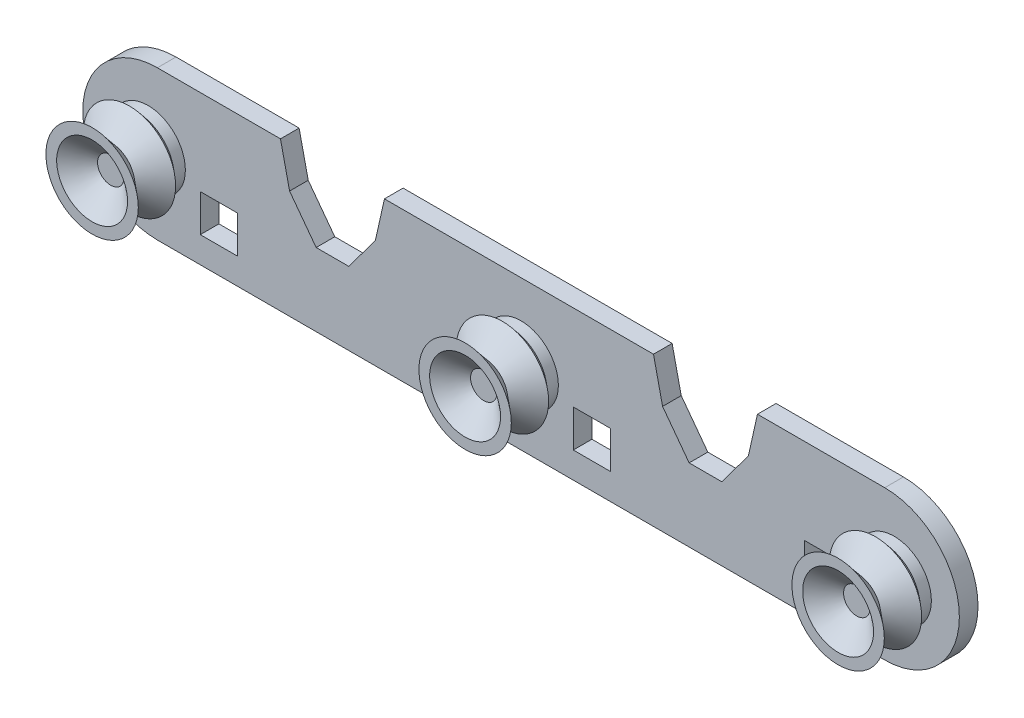
SolidWorks part; units mm, degrees
ref_plane "Plan de face" through (0, 0, 0) normal (0, 0, 1) x (1, 0, 0)
ref_plane "Plan de dessus" through (0, 0, 0) normal (0, 1, 0) x (1, 0, 0)
ref_plane "Plan de droite" through (0, 0, 0) normal (1, 0, 0) x (0, 0, -1)
sketch "Esquisse1" plane through (0, 0, 0) normal (0, 0, 1) x (1, 0, 0)
  line L0 (-98.7291, 0) -> (96.2709, 0) construction
  line L1 (-98.7291, 20) -> (96.2709, 20)
  line L2 (-98.7291, -20) -> (96.2709, -20)
  arc A0 (-98.7291, 20) -> (-98.7291, -20) centre (-98.7291, 0) ccw
  arc A1 (96.2709, -20) -> (96.2709, 20) centre (96.2709, 0) ccw
  circle A2 centre (-101.2291, 0) radius 5
  circle A3 centre (-1.2291, 0) radius 5
  circle A4 centre (98.7709, 0) radius 5
  point P3 (-1.2291, 0)
  point P8 (-118.7291, 0)
  point P9 (116.2709, 0)
  dimension "D1" = 235
  dimension "D2" = 20
  dimension "D3" = 10
  dimension "D4" = 10
  dimension "D5" = 10
  dimension "D6" = 100
  dimension "D7" = 100
extrude "Boss.-Extru.1" add sketch "Esquisse1" along normal blind 5
sketch "Esquisse2" plane through (0, 0, 5) normal (0, 0, 1) x (1, 0, 0)
  circle A0 centre (-101.2291, 0) radius 10
  circle A1 centre (-1.2291, 0) radius 10
  circle A2 centre (98.7709, 0) radius 10
  dimension "D1" = 20
  dimension "D2" = 3
extrude "Boss.-Extru.2" add sketch "Esquisse2" along normal blind 3
sketch "Esquisse3" plane through (0, 0, 8) normal (0, 0, 1) x (1, 0, 0)
  circle A0 centre (-101.2291, 0) radius 10
  circle A1 centre (-1.2291, 0) radius 10
  circle A2 centre (98.7709, 0) radius 10
  dimension "D1" = 3
extrude "Boss.-Extru.3" add sketch "Esquisse3" along normal blind 2 draft 50 draft outward yes
sketch "Esquisse4" plane through (0, 0, 10) normal (0, 0, 1) x (1, 0, 0)
  circle A0 centre (-101.2291, 0) radius 12.3835
  circle A1 centre (-1.2291, 0) radius 12.3835
  circle A2 centre (98.7709, 0) radius 12.3835
  dimension "D1" = 3
extrude "Boss.-Extru.4" add sketch "Esquisse4" along normal blind 5 draft 50
sketch "Esquisse5" plane through (0, 0, 15) normal (0, 0, 1) x (1, 0, 0)
  circle A0 centre (-101.2291, 0) radius 6.4247
  circle A1 centre (-1.2291, 0) radius 6.4247
  circle A2 centre (98.7709, 0) radius 6.4247
  dimension "D1" = 3
extrude "Boss.-Extru.5" add sketch "Esquisse5" along normal blind 5 draft 50 draft outward yes
sketch "Esquisse6" plane through (0, 0, 20) normal (0, 0, 1) x (1, 0, 0)
  circle A0 centre (-101.2291, 0) radius 9.5
  circle A1 centre (-1.2291, 0) radius 9.5
  circle A2 centre (98.7709, 0) radius 9.5
  dimension "D1" = 19
  dimension "D2" = 3
extrude "Enlèv. mat.-Extru.1" cut sketch "Esquisse6" against normal blind 5 draft 50
sketch "Esquisse7" plane through (0, 0, 0) normal (0, 0, -1) x (-1, 0, 0)
  line L0 (98.7291, -20) -> (-96.2709, -20) construction
  line L1 (-74.7709, -13) -> (-84.7709, -13)
  line L2 (-74.7709, -13) -> (-74.7709, -3)
  line L3 (-74.7709, -3) -> (-84.7709, -3)
  line L4 (-84.7709, -13) -> (-84.7709, -3)
  line L13 (65.7291, 20) -> (63.2907, 9.0964)
  line L14 (-12.7709, -13) -> (-22.7709, -13)
  line L15 (-12.7709, -13) -> (-12.7709, -3)
  line L16 (-12.7709, -3) -> (-22.7709, -3)
  line L17 (-22.7709, -13) -> (-22.7709, -3)
  line L18 (87.2291, -13) -> (77.2291, -13)
  line L19 (87.2291, -13) -> (87.2291, -3)
  line L20 (87.2291, -3) -> (77.2291, -3)
  line L21 (77.2291, -13) -> (77.2291, -3)
  line L22 (-96.2709, 20) -> (98.7291, 20) construction
  line L23 (63.2907, 9.0964) -> (56.1657, -0.4559)
  line L24 (56.1657, -0.4559) -> (47.4178, -0.4559) construction
  line L25 (51.7918, -0.4559) -> (51.7918, 22.851) construction
  line L30 (56.1657, -0.4559) -> (51.7918, -0.4559)
  line L31 (37.8545, 20) -> (40.2928, 9.0964)
  line L32 (40.2928, 9.0964) -> (47.4178, -0.4559)
  line L33 (47.4178, -0.4559) -> (51.7918, -0.4559)
  line L34 (65.7291, 20) -> (37.8545, 20)
  line L36 (-36.7093, 9.0964) -> (-43.8343, -0.4559)
  line L37 (-34.2709, 20) -> (-36.7093, 9.0964)
  line L38 (-52.5822, -0.4559) -> (-48.2082, -0.4559)
  line L39 (-43.8343, -0.4559) -> (-48.2082, -0.4559)
  line L40 (-59.7072, 9.0964) -> (-52.5822, -0.4559)
  line L41 (-62.1455, 20) -> (-59.7072, 9.0964)
  line L42 (-34.2709, 20) -> (-62.1455, 20)
  line L44 (-34.2709, 20) -> (-62.1455, 20) [skipped]
  circle A0 centre (-98.7709, 0) radius 5 construction
  circle A1 centre (1.2291, 0) radius 5 construction
  circle A2 centre (101.2291, 0) radius 5 construction
  point P16 (1.2291, 0)
  point P20 (101.2291, 0)
  point P31 (0, 0)
  point P32 (0, 0)
  point P36 (0, 0)
  point P39 (0, 0)
  dimension "D1" = 10
  dimension "D2" = 10
  dimension "D3" = 14
  dimension "D4" = 7
  dimension "D5" = 10
  dimension "D6" = 10
  dimension "D7" = 10
  dimension "D8" = 10
  dimension "D9" = 7
  dimension "D10" = 14
  dimension "D11" = 14
  dimension "D12" = 7
  dimension "D13" = 33
  dimension "D14" = 2
extrude "Enlèv. mat.-Extru.2" cut sketch "Esquisse7" against normal blind 10
